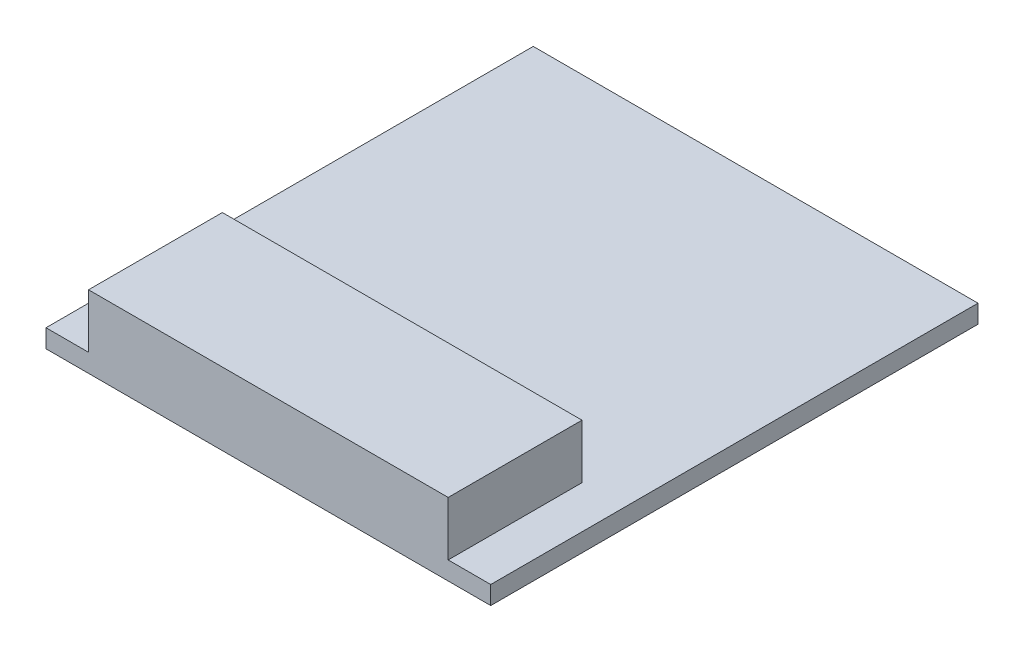
SolidWorks part; units mm, degrees
ref_plane "Front Plane" through (0, 0, 0) normal (0, 0, 1) x (1, 0, 0)
ref_plane "Top Plane" through (0, 0, 0) normal (0, 1, 0) x (1, 0, 0)
ref_plane "Right Plane" through (0, 0, 0) normal (1, 0, 0) x (0, 0, -1)
sketch "Sketch1" plane through (0, 0, 0) normal (0, 1, 0) x (1, 0, 0)
  line L7 (-4.605, -1.502) -> (10, -1.502)
  line L8 (-4.605, -1.502) -> (-4.605, 14.5)
  line L9 (-4.605, 14.5) -> (10, 14.5)
  line L10 (10, -1.502) -> (10, 14.5)
  line L11 (-4.605, -1.502) -> (10, 14.5) construction
  line L12 (-4.605, 14.5) -> (10, -1.502) construction
  point P0 (0, 0)
  point P6 (2.6975, 6.499)
  dimension "D3" = 14.605
  dimension "D4" = 16.002
extrude "Boss-Extrude1" add sketch "Sketch1" along normal blind 0.6 contours L9 L10 L7 L8
sketch "Sketch2" plane through (0, 0.6, 0) normal (0, 1, 0) x (1, 0, 0)
  line L0 (-4.605, -1.502) -> (10, -1.502) construction
  line L1 (-3.208, 2.8922) -> (8.603, 2.8922)
  line L2 (-3.208, 2.8922) -> (-3.208, -1.502)
  line L3 (-3.208, -1.502) -> (8.603, -1.502)
  line L4 (8.603, 2.8922) -> (8.603, -1.502)
  line L5 (-3.208, 2.8922) -> (8.603, -1.502) construction
  line L6 (-3.208, -1.502) -> (8.603, 2.8922) construction
  point P0 (2.6975, 0.6951)
  point P7 (2.6975, -1.502)
  dimension "D1" = 11.811
  dimension "D2" = 4.3942
extrude "Boss-Extrude2" add sketch "Sketch2" along normal blind 1.778
sketch "Sketch3" plane through (0, 0.6, 0) normal (0, 1, 0) x (1, 0, 0)
  line L0 (-4.605, -1.502) -> (-4.605, 14.5) construction
  line L1 (-3.716, 12.468) -> (-1.176, 12.468)
  line L2 (-3.716, 12.468) -> (-3.716, 7.388)
  line L3 (-3.716, 7.388) -> (-1.176, 7.388)
  line L4 (-1.176, 12.468) -> (-1.176, 7.388)
  line L5 (-3.716, 12.468) -> (-1.176, 7.388) construction
  line L6 (-3.716, 7.388) -> (-1.176, 12.468) construction
  line L9 (-4.605, -1.502) -> (-3.208, -1.502) construction
  line L10 (-0.286, 12.468) -> (2.254, 12.468)
  line L11 (-0.286, 12.468) -> (-0.286, 7.388)
  line L12 (2.254, 12.468) -> (2.254, 7.388)
  line L13 (-0.286, 7.388) -> (2.254, 7.388)
  line L14 (3.144, 12.468) -> (5.684, 12.468)
  line L15 (3.144, 12.468) -> (3.144, 7.388)
  line L16 (5.684, 12.468) -> (5.684, 7.388)
  line L17 (3.144, 7.388) -> (5.684, 7.388)
  line L18 (6.574, 12.468) -> (9.114, 12.468)
  line L19 (6.574, 12.468) -> (6.574, 7.388)
  line L20 (9.114, 12.468) -> (9.114, 7.388)
  line L21 (6.574, 7.388) -> (9.114, 7.388)
  point P0 (-2.446, 9.928)
  dimension "D1" = 2.159
  dimension "D2" = 11.43
  dimension "D3" = 5.08
  dimension "D4" = 2.54
  dimension "D5" = 4
